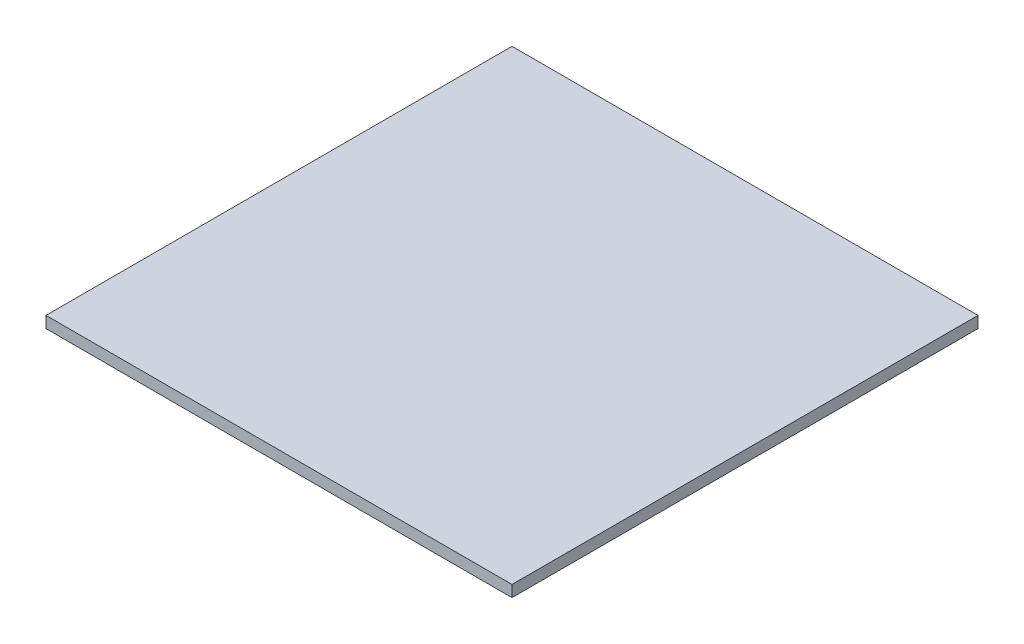
SolidWorks part; units mm, degrees
ref_plane "Front" through (0, 0, 0) normal (0, 0, 1) x (1, 0, 0)
ref_plane "Top" through (0, 0, 0) normal (0, 1, 0) x (1, 0, 0)
ref_plane "Right" through (0, 0, 0) normal (1, 0, 0) x (0, 0, -1)
sketch "Sketch1" plane through (0, 0, 0) normal (0, 1, 0) x (1, 0, 0)
  line L1 (-61, -61) -> (61, -61)
  line L2 (-61, -61) -> (-61, 61)
  line L3 (-61, 61) -> (61, 61)
  line L4 (61, -61) -> (61, 61)
  line L5 (-61, -61) -> (61, 61) construction
  line L6 (-61, 61) -> (61, -61) construction
  point P0 (0, 0)
  dimension "D1" = 122
  dimension "D2" = 122
extrude "Boss-Extrude1" add sketch "Sketch1" along normal blind 3
